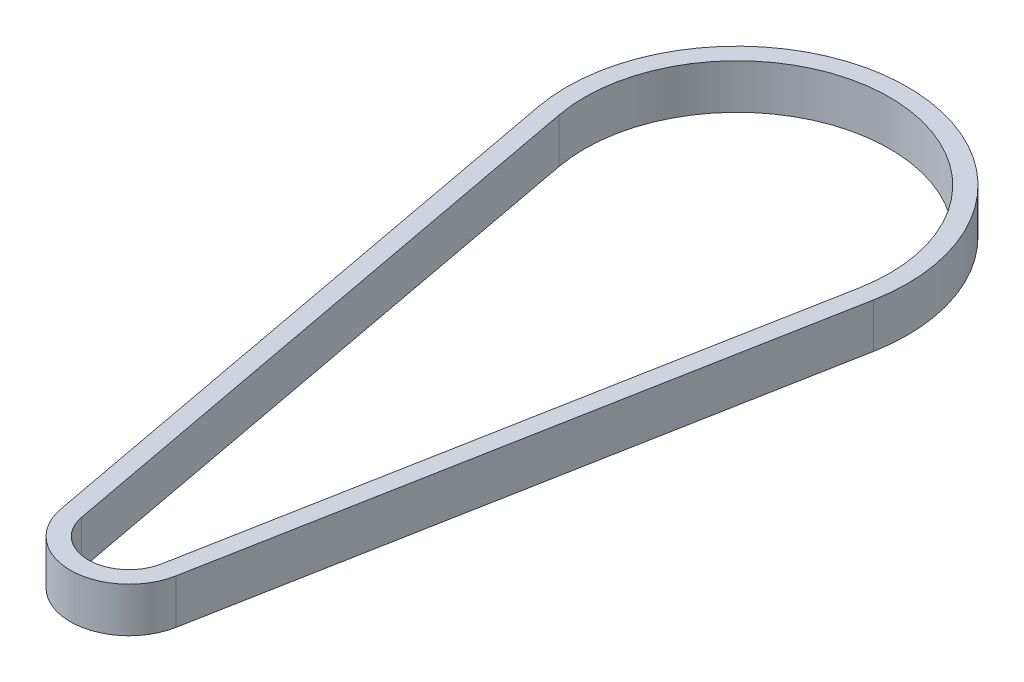
SolidWorks part; units mm, degrees
ref_plane "Front Plane" through (0, 0, 0) normal (0, 0, 1) x (1, 0, 0)
ref_plane "Top Plane" through (0, 0, 0) normal (0, 1, 0) x (1, 0, 0)
ref_plane "Right Plane" through (0, 0, 0) normal (1, 0, 0) x (0, 0, -1)
sketch "Sketch1" plane through (0, 0, 0) normal (0, 1, 0) x (1, 0, 0)
  line L0 (0, 0) -> (0, -680.8) construction
  line L1 (-167.8472, -31.351) -> (-44.9722, -689.2)
  line L2 (167.8472, -31.351) -> (44.9722, -689.2)
  line L3 (-187.5072, -35.0231) -> (-64.6322, -692.8722)
  line L4 (187.5072, -35.0231) -> (64.6322, -692.8722)
  arc A0 (167.8472, -31.351) -> (-167.8472, -31.351) centre (0, 0) ccw
  arc A1 (-44.9722, -689.2) -> (44.9722, -689.2) centre (0, -680.8) ccw
  arc A2 (187.5072, -35.0231) -> (-187.5072, -35.0231) centre (0, 0) ccw
  arc A3 (-64.6322, -692.8722) -> (64.6322, -692.8722) centre (0, -680.8) ccw
  dimension "D1" = 341.5
  dimension "D2" = 91.5
  dimension "D3" = 680.8
  dimension "D4" = 20
extrude "Boss-Extrude1" add sketch "Sketch1" along normal blind 50 contours L3 A3 L4 A2 A1 L1 A0 L2
